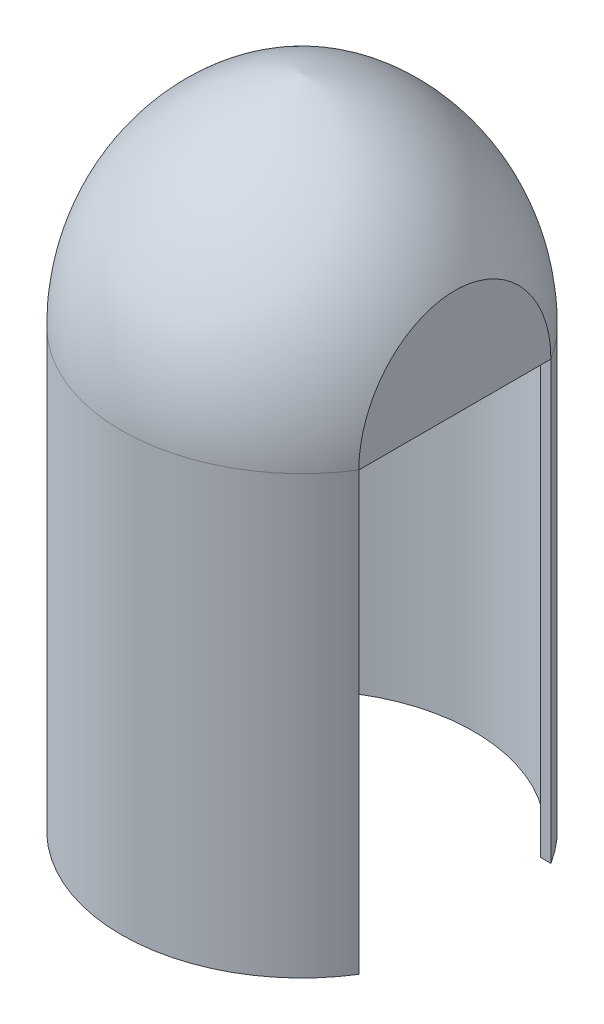
SolidWorks part; units mm, degrees
ref_plane "Front Plane" through (0, 0, 0) normal (0, 0, 1) x (1, 0, 0)
ref_plane "Top Plane" through (0, 0, 0) normal (0, 1, 0) x (1, 0, 0)
ref_plane "Right Plane" through (0, 0, 0) normal (1, 0, 0) x (0, 0, -1)
sketch "Sketch1" plane through (0, 0, 0) normal (0, 0, 1) x (1, 0, 0)
  line L0 (62, 0) -> (59, 0)
  line L2 (0, 75) -> (0, 71.9432)
  arc A0 (62, 0) -> (0, 75) centre (-14.3629, 0) ccw
  arc A1 (59, 0) -> (0, 71.9432) centre (-14.3629, 0) ccw
  arc A2 (59, 0) -> (-0.5643, 72.0535) centre (-14.3629, 0) ccw construction
  dimension "D1" = 3
  dimension "D2" = 62
  dimension "D3" = 75
revolve "Revolve1" add sketch "Sketch1" angle 360 about L2
sketch "Sketch2" plane through (0, 0, 0) normal (0, -1, 0) x (-1, 0, 0)
  line L1 (52.5, 72.8837) -> (-52.5, 72.8837)
  line L2 (52.5, 72.8837) -> (52.5, -72.8837)
  line L3 (52.5, -72.8837) -> (-52.5, -72.8837)
  line L4 (-52.5, 72.8837) -> (-52.5, -72.8837)
  line L5 (52.5, 72.8837) -> (-52.5, -72.8837) construction
  line L6 (52.5, -72.8837) -> (-52.5, 72.8837) construction
  point P0 (0, 0)
  dimension "D1" = 105
  dimension "D2" = 145.7674
extrude "Cut-Extrude2" cut sketch "Sketch2" against normal through all flip side to cut
sketch "Sketch3" plane through (0, 0, 0) normal (0, -1, 0) x (1, 0, 0)
  line L0 (-52.5, 32.9811) -> (-48.9209, 32.9811)
  line L1 (-48.9209, 32.9811) -> (-48.9209, -32.9811)
  line L2 (-48.9209, -32.9811) -> (-52.5, -32.9811)
  line L3 (-52.5, -32.9811) -> (-52.5, 32.9811)
  line L4 (0, 0) -> (0, 17.4115) construction
  line L5 (48.9209, -32.9811) -> (52.5, -32.9811)
  line L6 (52.5, 32.9811) -> (48.9209, 32.9811)
  line L7 (52.5, -32.9811) -> (52.5, 32.9811)
  line L8 (48.9209, 32.9811) -> (48.9209, -32.9811)
  arc A0 (52.5, 26.9212) -> (-52.5, 26.9212) centre (0, 0) ccw construction
  arc A1 (-52.5, -26.9212) -> (52.5, -26.9212) centre (0, 0) ccw construction
extrude "Boss-Extrude2" add sketch "Sketch3" against normal up to surface
sketch "Sketch4" plane through (0, 0, 0) normal (0, -1, 0) x (-1, 0, 0)
  line L0 (52.5007, -32.98) -> (48.9216, -32.98)
  line L2 (-48.9216, -32.98) -> (-52.5007, -32.98)
  line L3 (0, 0) -> (-30.1101, 0) construction
  line L5 (-48.9216, 32.98) -> (-52.5007, 32.98)
  line L6 (52.5007, 32.98) -> (48.9216, 32.98)
  arc A1 (-48.9216, -32.98) -> (48.9216, -32.98) centre (0, 0) ccw
  arc A2 (-52.5007, -32.98) -> (52.5007, -32.98) centre (0, 0) ccw
  arc A3 (-49.9603, -31.3842) -> (49.9603, -31.3842) centre (0, 0) ccw construction
  arc A4 (-52.5007, 32.98) -> (52.5007, 32.98) centre (0, 0) cw
  arc A5 (-48.9216, 32.98) -> (48.9216, 32.98) centre (0, 0) cw
  dimension "D2" = 62
  dimension "D3" = 32.98
  dimension "D1" = 3
extrude "Boss-Extrude4" add sketch "Sketch4" along normal blind 150
